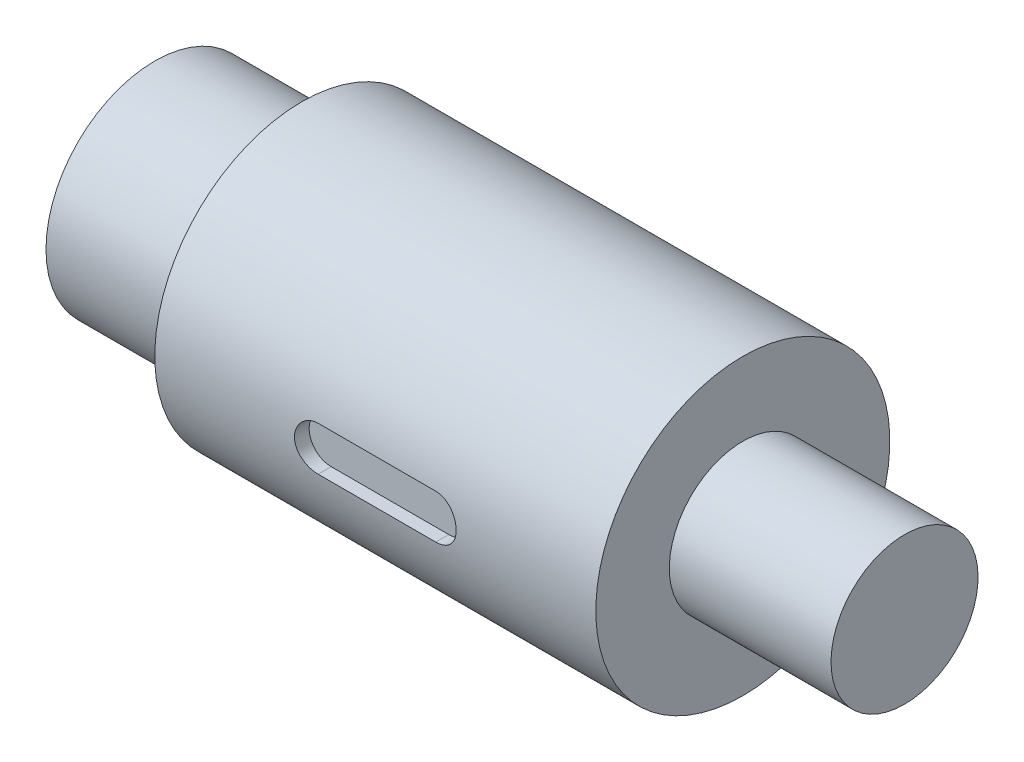
SolidWorks part; units mm, degrees
ref_plane "Front Plane" through (0, 0, 0) normal (0, 0, 1) x (1, 0, 0)
ref_plane "Top Plane" through (0, 0, 0) normal (0, 1, 0) x (1, 0, 0)
ref_plane "Right Plane" through (0, 0, 0) normal (1, 0, 0) x (0, 0, -1)
sketch "Sketch1" plane through (0, 0, 0) normal (0, 0, 1) x (1, 0, 0)
  line L0 (0, 0) -> (0, 7.4)
  line L1 (0, 7.4) -> (10, 7.4)
  line L2 (10, 7.4) -> (10, 10)
  line L3 (10, 10) -> (40, 10)
  line L4 (40, 10) -> (40, 5)
  line L5 (40, 5) -> (51, 5)
  line L6 (51, 5) -> (51, 0)
  line L7 (0, 0) -> (51, 0)
  dimension "D1" = 7.4
  dimension "D2" = 10
  dimension "D3" = 5
  dimension "D4" = 10
  dimension "D5" = 30
  dimension "D6" = 11
revolve "Revolve1" add sketch "Sketch1" angle 360 about L7
sketch "Sketch2" plane through (0, 0, 0) normal (0, 0, 1) x (1, 0, 0)
  line L0 (0, 0) -> (39.9824, 0) construction
  line L1 (0, 7.4) -> (0, -7.4) construction
  line L2 (21, 0) -> (29, 0) construction
  line L3 (21, 1.5) -> (29, 1.5)
  line L4 (21, -1.5) -> (29, -1.5)
  line L5 (25, 10) -> (25, -14.9714) construction
  line L6 (40, 10) -> (10, 10) construction
  arc A0 (21, 1.5) -> (21, -1.5) centre (21, 0) ccw
  arc A1 (29, -1.5) -> (29, 1.5) centre (29, 0) ccw
  point P6 (25, 0)
  point P11 (25, 0)
  dimension "D2" = 1.5
  dimension "D1" = 8
extrude "Cut-Extrude1" cut sketch "Sketch2" along normal blind 10 from offset 9
